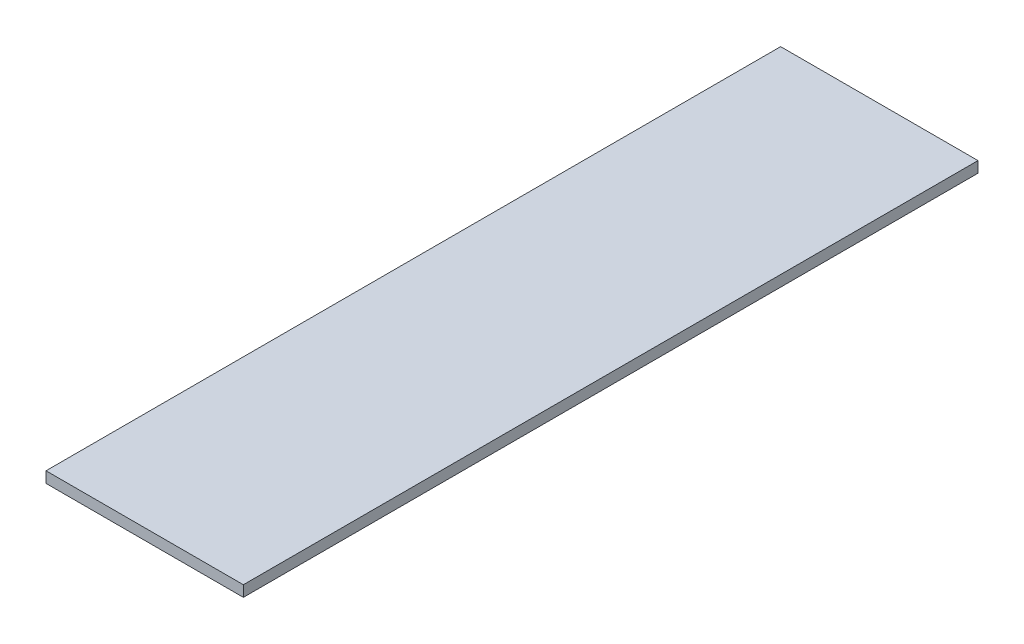
SolidWorks part; units mm, degrees
ref_plane "Front Plane" through (0, 0, 0) normal (0, 0, 1) x (1, 0, 0)
ref_plane "Top Plane" through (0, 0, 0) normal (0, 1, 0) x (1, 0, 0)
ref_plane "Right Plane" through (0, 0, 0) normal (1, 0, 0) x (0, 0, -1)
sketch "Sketch1" plane through (0, 0, 0) normal (0, 1, 0) x (1, 0, 0)
  line L1 (0, 0) -> (57.15, 0)
  line L2 (0, 0) -> (0, 212.725)
  line L3 (0, 212.725) -> (57.15, 212.725)
  line L4 (57.15, 0) -> (57.15, 212.725)
  dimension "D1" = 212.725
  dimension "D2" = 57.15
extrude "Boss-Extrude1" add sketch "Sketch1" along normal blind 3.175
